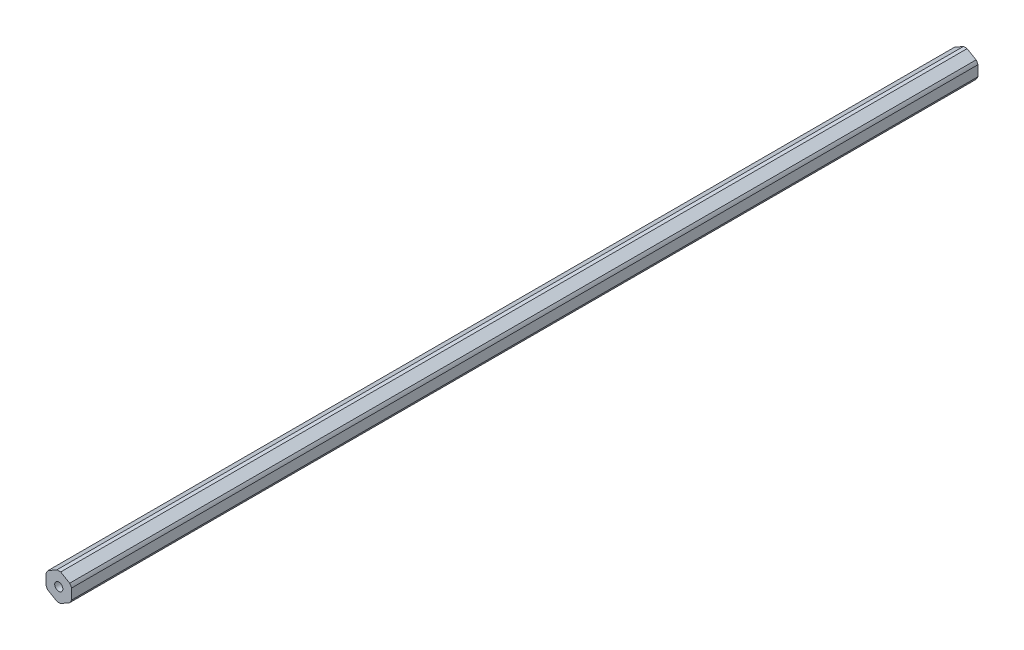
SolidWorks part; units mm, degrees
ref_plane "Front Plane" through (0, 0, 0) normal (0, 0, 1) x (1, 0, 0)
ref_plane "Top Plane" through (0, 0, 0) normal (0, 1, 0) x (1, 0, 0)
ref_plane "Right Plane" through (0, 0, 0) normal (1, 0, 0) x (0, 0, -1)
sketch "Sketch1" plane through (0, 0, 0) normal (0, 0, 1) x (1, 0, 0)
  line L1 (6.35, 3.6662) -> (0, 7.3323)
  line L2 (0, 7.3323) -> (-6.35, 3.6662)
  line L3 (-6.35, 3.6662) -> (-6.35, -3.6662)
  line L4 (-6.35, -3.6662) -> (0, -7.3323)
  line L5 (0, -7.3323) -> (6.35, -3.6662)
  line L6 (6.35, -3.6662) -> (6.35, 3.6662)
  circle A0 centre (0, 0) radius 6.35 construction
  circle A1 centre (0, 0) radius 6.858
  dimension "D1" = 12.7
  dimension "D2" = 13.716
extrude "Boss-Extrude1" add sketch "Sketch1" along normal mid plane 450.85 contours L6 A1 L1 L2 L3 L4 L5
hole_wizard "#10-32 Tapped Hole1" positions "3DSketch1" profile "Sketch2" tap size "#10-32" standard "ANSI Inch"
sketch3d "3DSketch1"
  line L0 (0, 0, 225.425) -> (0, 0, -225.425) construction
  point P0 (0, 0, 225.425)
  point P4 (0, 0, -225.425)
sketch "Sketch2" plane through (0, 0, 225.425) normal (1, 0, 0) x (0, -1, 0)
  line L0 (0, 0) -> (0, 16.2908)
  line L1 (0, 16.2908) -> (2.0193, 15.0774)
  line L2 (2.0193, 15.0774) -> (2.0193, 0)
  line L5 (2.0193, 0) -> (0, 0)
  line L10 (0, 16.2908) -> (-2.0193, 15.0774) construction
  line L11 (0, -6.35) -> (0, 107.95) construction
  dimension "Tap Drill Dia." = 4.0386
  dimension "Tap Drill Depth" = 15.0774
  dimension "Drill Angle" = 118
cosmetic thread "Hole Thread1" parameters "D1"=12.7, "D2"=4.826
cosmetic thread "Hole Thread2" parameters "D1"=12.7, "D2"=4.826
